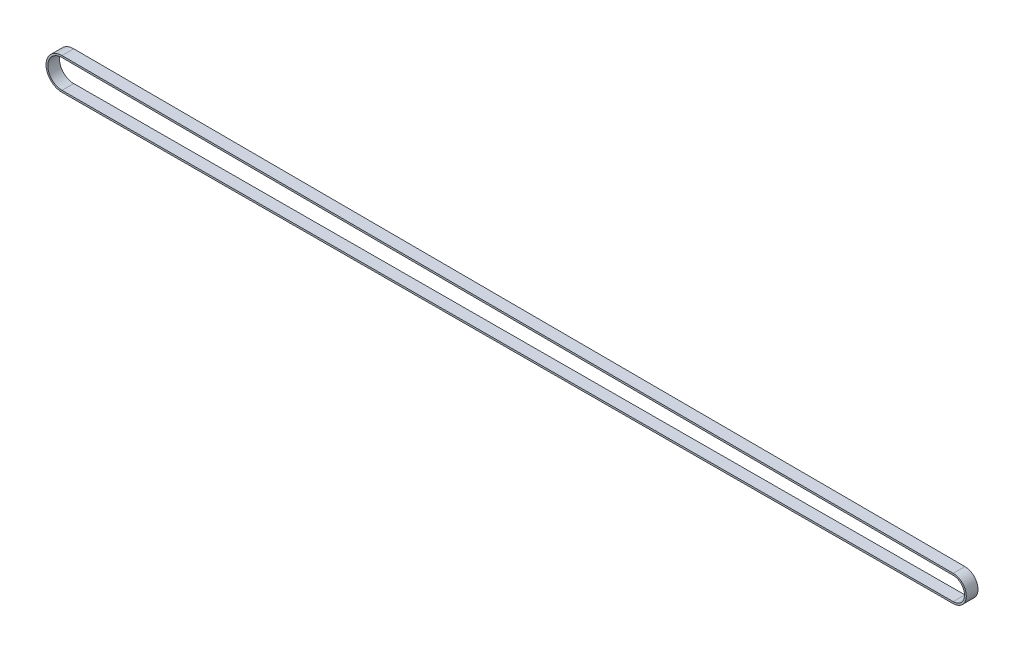
SolidWorks part; units mm, degrees
ref_plane "Front Plane" through (0, 0, 0) normal (0, 0, 1) x (1, 0, 0)
ref_plane "Top Plane" through (0, 0, 0) normal (0, 1, 0) x (1, 0, 0)
ref_plane "Right Plane" through (0, 0, 0) normal (1, 0, 0) x (0, 0, -1)
sketch "Sketch2" plane through (0, 0, 0) normal (0, 0, 1) x (1, 0, 0)
  line L0 (0, 0) -> (1, 0) construction
  line L1 (0, 0) -> (0, 1) construction
  line L2 (0.0165, -17.5469) -> (-380.4797, -18.7469)
  line L3 (-380.4797, -5.8849) -> (0.0165, -7.0849)
  arc A0 (0.0165, -7.0849) -> (0.0165, -17.5469) centre (0, -12.3159) cw
  arc A1 (-380.4797, -18.7469) -> (-380.4797, -5.8849) centre (-380.5, -12.3159) cw
extrude "Extrude-Thin1" add sketch "Sketch2" along normal mid plane 5 thin thin type mid plane wall 0.762
